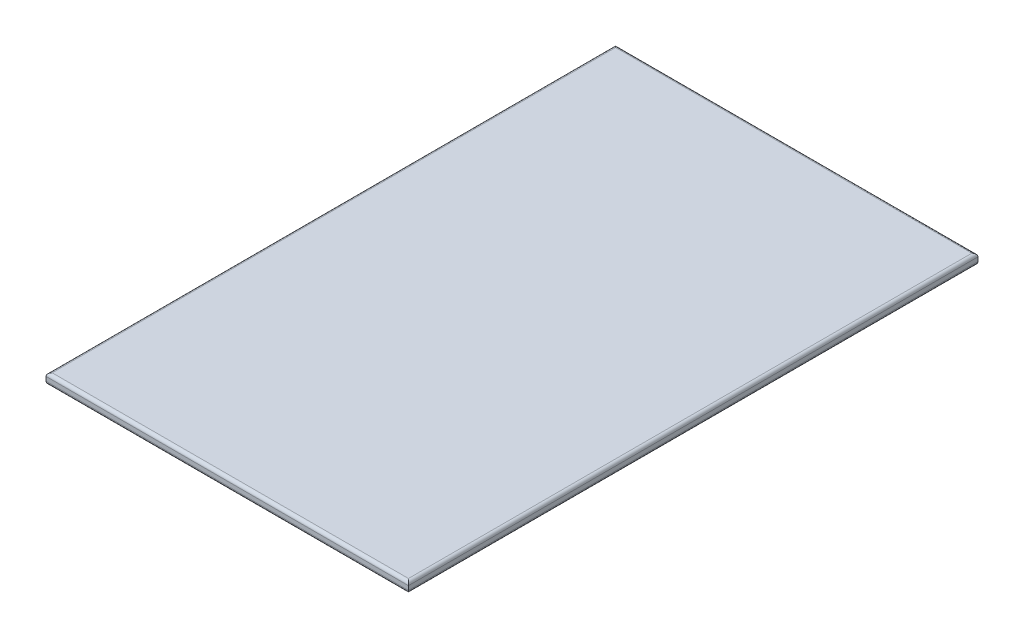
SolidWorks part; units mm, degrees
ref_plane "Front" through (0, 0, 0) normal (0, 0, 1) x (1, 0, 0)
ref_plane "Top" through (0, 0, 0) normal (0, 1, 0) x (1, 0, 0)
ref_plane "Right" through (0, 0, 0) normal (1, 0, 0) x (0, 0, -1)
sketch "Sketch1" plane through (0, 0, 0) normal (0, 1, 0) x (1, 0, 0)
  line L1 (-17.5, 27.5) -> (17.5, 27.5)
  line L2 (-17.5, 27.5) -> (-17.5, -27.5)
  line L3 (-17.5, -27.5) -> (17.5, -27.5)
  line L4 (17.5, 27.5) -> (17.5, -27.5)
  line L5 (-17.5, 27.5) -> (17.5, -27.5) construction
  line L6 (-17.5, -27.5) -> (17.5, 27.5) construction
  point P0 (0, 0)
  dimension "D1" = 55
  dimension "D2" = 35
extrude "Boss-Extrude1" add sketch "Sketch1" along normal blind 1
fillet "Fillet3" radius 0.3 8 edges at (0, 0, -27.5) (-17.5, 0, 0) (0, 0, 27.5) (17.5, 0, 0) (0, 1, 27.5) (-17.5, 1, 0) (0, 1, -27.5) (17.5, 1, 0)
